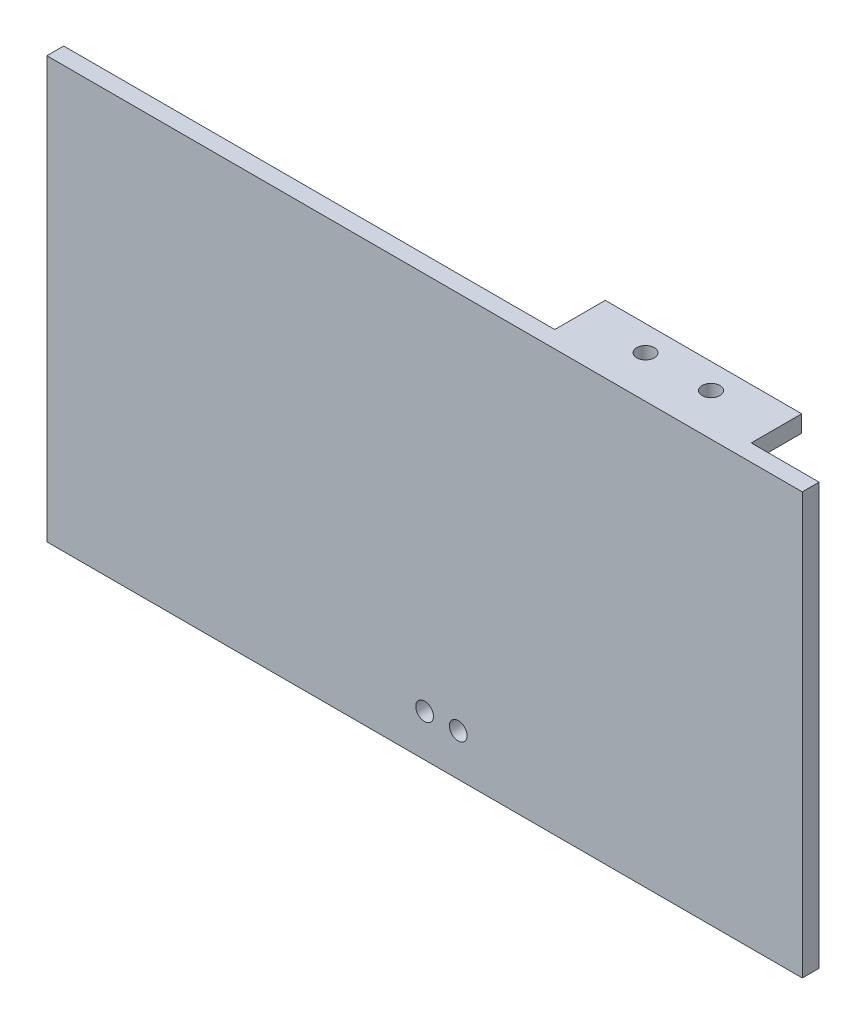
SolidWorks part; units mm, degrees
ref_plane "Front Plane" through (0, 0, 0) normal (0, 0, 1) x (1, 0, 0)
ref_plane "Top Plane" through (0, 0, 0) normal (0, 1, 0) x (1, 0, 0)
ref_plane "Right Plane" through (0, 0, 0) normal (1, 0, 0) x (0, 0, -1)
sketch "Sketch1" plane through (0, 0, 0) normal (0, 1, 0) x (1, 0, 0)
  line L1 (0, 0) -> (134.58, 0)
  line L2 (0, 0) -> (0, 3)
  line L3 (0, 3) -> (134.58, 3)
  line L4 (134.58, 0) -> (134.58, 3)
  dimension "D1" = 3
  dimension "D2" = 134.58
extrude "Boss-Extrude1" add sketch "Sketch1" along normal blind 75
sketch "Sketch2" plane through (0, 0, -3) normal (0, 0, -1) x (-1, 0, 0)
  line L0 (-134.58, 75) -> (0, 75) construction
  line L1 (-122.48, 75) -> (-87.48, 75)
  line L2 (-122.48, 75) -> (-122.48, 72)
  line L3 (-122.48, 72) -> (-87.48, 72)
  line L4 (-87.48, 75) -> (-87.48, 72)
  line L5 (-134.58, 75) -> (-134.58, 0) construction
  dimension "D1" = 12.1
  dimension "D2" = 3
  dimension "D3" = 35
extrude "Boss-Extrude2" add sketch "Sketch2" along normal blind 9
sketch "Sketch3" plane through (0, 75, 0) normal (0, 1, 0) x (1, 0, 0)
  line L0 (87.48, 12) -> (122.48, 12) construction
  line L1 (87.48, 12) -> (87.48, 3) construction
  line L3 (122.48, 12) -> (122.48, 3) construction
  circle A0 centre (110.8133, 7.5) radius 1.575
  circle A1 centre (99.1467, 7.5) radius 1.575
  dimension "D1" = 3.15
  dimension "D2" = 3.15
  dimension "D3" = 4.5
  dimension "D4" = 4.5
  dimension "D5" = 11.6667
  dimension "D6" = 11.6667
extrude "Cut-Extrude1" cut sketch "Sketch3" against normal through all
sketch "Sketch4" plane through (0, 0, 0) normal (0, 0, 1) x (1, 0, 0)
  line L0 (0, 0) -> (134.58, 0) construction
  line L2 (134.58, 75) -> (134.58, 0) construction
  circle A0 centre (73.29, 7.5) radius 1.575
  circle A1 centre (67.29, 7.5) radius 1.575
  dimension "D1" = 3.15
  dimension "D2" = 3.15
  dimension "D3" = 6
  dimension "D4" = 7.5
  dimension "D5" = 7.5
  dimension "D6" = 61.29
extrude "Cut-Extrude2" cut sketch "Sketch4" against normal through all
